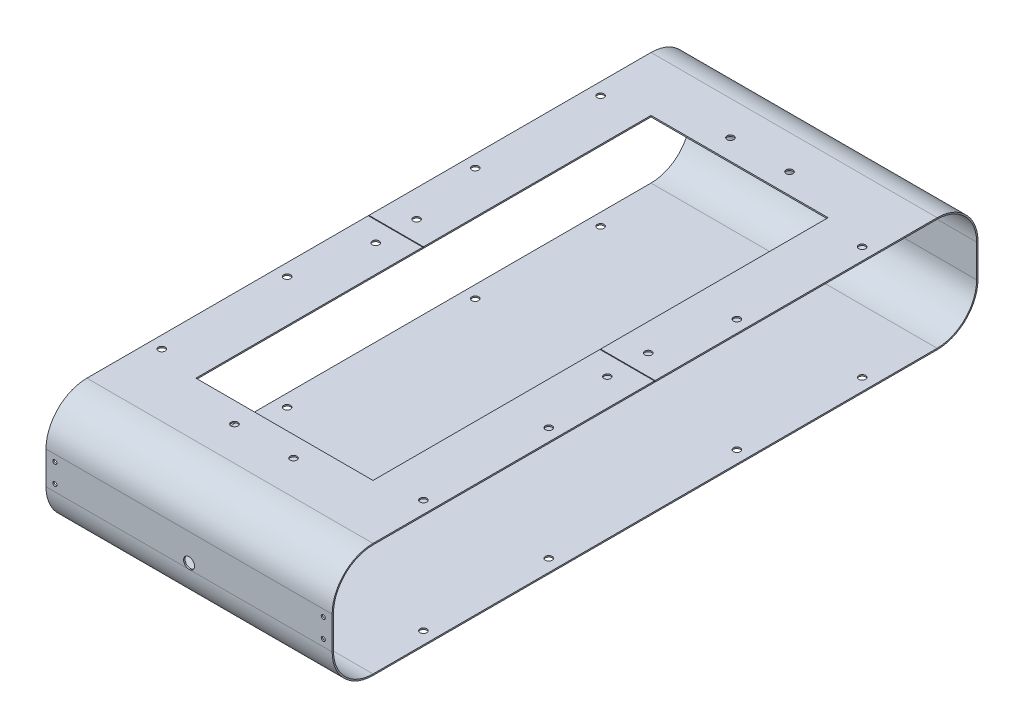
SolidWorks part; units mm, degrees
material "3.0205 (EN-AW 1200)"
ref_plane "Alzado" through (0, 0, 0) normal (0, 0, 1) x (1, 0, 0)
ref_plane "Planta" through (0, 0, 0) normal (0, 1, 0) x (1, 0, 0)
ref_plane "Vista lateral" through (0, 0, 0) normal (1, 0, 0) x (0, 0, -1)
sketch "Croquis1" plane through (0, 0, 0) normal (1, 0, 0) x (0, 0, -1)
  line L1 (207, -42) -> (-207, -42)
  line L2 (237, -12) -> (237, 12)
  line L3 (207, 42) -> (-207, 42)
  line L4 (-237, -12) -> (-237, 12)
  line L5 (237, -42) -> (-237, 42) construction
  line L6 (237, 42) -> (-237, -42) construction
  arc A4 (-237, 12) -> (-207, 42) centre (-207, 12) cw
  arc A5 (207, -42) -> (237, -12) centre (207, -12) ccw
  arc A6 (207, 42) -> (237, 12) centre (207, 12) cw
  arc A7 (-237, -12) -> (-207, -42) centre (-207, -12) ccw
  point P0 (0, 0)
  dimension "D4" = 30
  dimension "D5" = 30
  dimension "D1" = 474
  dimension "D2" = 84
extrude "Saliente-Extruir1" add sketch "Croquis1" along normal mid plane 220
shell "Vaciado2" thickness 1
sketch "Croquis2" plane through (110, 0, 0) normal (1, 0, 0) x (0, 0, -1)
  line L8 (237, -12) -> (237, 12)
  line L9 (207, 42) -> (-207, 42)
  line L10 (-237, 12) -> (-237, -12)
  line L11 (-207, -42) -> (207, -42)
  line L12 (237, -12) -> (237, 12)
  line L13 (207, 42) -> (-207, 42)
  line L14 (-237, 12) -> (-237, -12)
  line L15 (-207, -42) -> (207, -42)
  arc A8 (207, -42) -> (237, -12) centre (207, -12) ccw
  arc A9 (237, 12) -> (207, 42) centre (207, 12) ccw
  arc A10 (-207, 42) -> (-237, 12) centre (-207, 12) ccw
  arc A11 (-237, -12) -> (-207, -42) centre (-207, -12) ccw
  arc A12 (207, -42) -> (237, -12) centre (207, -12) ccw
  arc A13 (237, 12) -> (207, 42) centre (207, 12) ccw
  arc A14 (-207, 42) -> (-237, 12) centre (-207, 12) ccw
  arc A15 (-237, -12) -> (-207, -42) centre (-207, -12) ccw
  dimension "D1" = 0
sketch "Croquis5" plane through (0, 0, 0) normal (1, 0, 0) x (0, 0, -1)
  line L27 (-237, 12) -> (-237, -12)
  line L28 (-207, -42) -> (207, -42)
  line L29 (237, -12) -> (237, 12)
  line L30 (207, 42) -> (-207, 42)
  line L31 (-237, 12) -> (-237, -12)
  line L32 (-207, -42) -> (207, -42)
  line L33 (237, -12) -> (237, 12)
  line L34 (207, 42) -> (-207, 42)
  arc A31 (-237, -12) -> (-207, -42) centre (-207, -12) ccw
  arc A32 (207, -42) -> (237, -12) centre (207, -12) ccw
  arc A33 (237, 12) -> (207, 42) centre (207, 12) ccw
  arc A34 (-207, 42) -> (-237, 12) centre (-207, 12) ccw
  arc A35 (-237, -12) -> (-207, -42) centre (-207, -12) ccw
  arc A36 (207, -42) -> (237, -12) centre (207, -12) ccw
  arc A37 (237, 12) -> (207, 42) centre (207, 12) ccw
  arc A38 (-207, 42) -> (-237, 12) centre (-207, 12) ccw
  dimension "D1" = 0
sketch "Croquis6" plane through (-110, 0, 0) normal (-1, 0, 0) x (0, 0, 1)
  line L8 (207, 42) -> (-207, 42)
  line L9 (237, -12) -> (237, 12)
  line L10 (-207, -42) -> (207, -42)
  line L11 (-237, 12) -> (-237, -12)
  line L12 (207, 42) -> (-207, 42)
  line L13 (237, -12) -> (237, 12)
  line L14 (-207, -42) -> (207, -42)
  line L15 (-237, 12) -> (-237, -12)
  arc A8 (237, 12) -> (207, 42) centre (207, 12) ccw
  arc A9 (207, -42) -> (237, -12) centre (207, -12) ccw
  arc A10 (-237, -12) -> (-207, -42) centre (-207, -12) ccw
  arc A11 (-207, 42) -> (-237, 12) centre (-207, 12) ccw
  arc A12 (237, 12) -> (207, 42) centre (207, 12) ccw
  arc A13 (207, -42) -> (237, -12) centre (207, -12) ccw
  arc A14 (-237, -12) -> (-207, -42) centre (-207, -12) ccw
  arc A15 (-207, 42) -> (-237, 12) centre (-207, 12) ccw
  dimension "D1" = 0
extrude "Cortar-Extruir1" cut sketch "Croquis6" against normal blind 10
sketch "Croquis7" plane through (0, 0, 237) normal (0, 0, 1) x (1, 0, 0)
  line L0 (82.1341, 15) -> (-72.1341, 15)
  line L1 (-72.1341, -15) -> (82.1341, -15)
  line L2 (-72.1341, 15) -> (82.1341, -15) construction
  line L3 (82.1341, 15) -> (-72.1341, -15) construction
  line L4 (110, 12) -> (-100, -12) construction
  arc A0 (-74.8961, 14.1673) -> (-74.8961, -14.1673) centre (-65.5, 0) ccw
  arc A1 (84.8961, -14.1673) -> (84.8961, 14.1673) centre (75.5, 0) ccw
  spline S0 degree 2 poles (-72.1341, 15) (-72.8713, 15) (-73.5765, 14.7873) (-74.2822, 14.5745) (-74.8961, 14.1673) knots 0 0 0 0.5 0.5 1 1 1
  spline S1 degree 2 poles (-74.8961, -14.1673) (-74.2818, -14.5748) (-73.5765, -14.7873) (-72.8707, -15) (-72.1341, -15) knots 0 0 0 0.5 0.5 1 1 1
  spline S2 degree 2 poles (82.1341, -15) (82.8713, -15) (83.5765, -14.7873) (84.2822, -14.5745) (84.8961, -14.1673) knots 0 0 0 0.5 0.5 1 1 1
  spline S3 degree 2 poles (84.8961, 14.1673) (84.2818, 14.5748) (83.5765, 14.7873) (82.8707, 15) (82.1341, 15) knots 0 0 0 0.5 0.5 1 1 1
  point P16 (5, 0)
  point P17 (5, 0)
sketch "Croquis8" plane through (0, 0, 237) normal (0, 0, 1) x (1, 0, 0)
  line L0 (110, 12) -> (103.5, 12) construction
  line L1 (110, 12) -> (-100, 12) construction
  line L2 (103.5, 12) -> (103.5, 7) construction
  line L3 (110, -12) -> (103.5, -12) construction
  line L4 (110, -12) -> (-100, -12) construction
  line L5 (103.5, -12) -> (103.5, -7) construction
  line L6 (5, 0) -> (5, 71.8665) construction
  line L7 (-72.1341, 15) -> (82.1341, -15) construction
  circle A0 centre (103.5, 7) radius 1.5
  circle A1 centre (103.5, -7) radius 1.5
  circle A2 centre (-93.5, -7) radius 1.5
  circle A3 centre (-93.5, 7) radius 1.5
  dimension "D3" = 3
  dimension "D6" = 3
  dimension "D1" = 6.5
  dimension "D2" = 5
  dimension "D4" = 6.5
  dimension "D5" = 5
extrude "Cortar-Extruir4" cut sketch "Croquis8" against normal blind 5
sketch "Croquis9" plane through (0, 0, 237) normal (0, 0, 1) x (1, 0, 0)
  line L0 (5, -12) -> (5, -4) construction
  line L1 (110, -12) -> (-100, -12) construction
  circle A0 centre (5, -8) radius 4
  dimension "D1" = 8
extrude "Cortar-Extruir5" cut sketch "Croquis9" against normal blind 5
sketch "Croquis10" plane through (0, 42, 0) normal (0, 1, 0) x (1, 0, 0)
  line L0 (110, 207) -> (101, 207) construction
  line L1 (110, 207) -> (-100, 207) construction
  line L2 (101, 207) -> (101, 161.01) construction
  line L3 (101, 161.01) -> (101, 69.01) construction
  line L4 (5, 207) -> (5, -207) construction
  line L5 (110, -207) -> (-100, -207) construction
  line L6 (5, 0) -> (-100, 0) construction
  line L7 (-100, -207) -> (-100, 207) construction
  line L8 (-91, 161.01) -> (-91, 69.01) construction
  line L9 (-91, 207) -> (-91, 161.01) construction
  line L10 (101, -161.01) -> (101, -69.01) construction
  line L11 (101, -207) -> (101, -161.01) construction
  line L12 (-91, -161.01) -> (-91, -69.01) construction
  circle A0 centre (101, 161.01) radius 2.5
  circle A1 centre (101, 69.01) radius 2.5
  circle A2 centre (-91, 69.01) radius 2.5
  circle A3 centre (-91, 161.01) radius 2.5
  circle A4 centre (101, -69.01) radius 2.5
  circle A5 centre (101, -161.01) radius 2.5
  circle A6 centre (-91, -161.01) radius 2.5
  circle A7 centre (-91, -69.01) radius 2.5
  dimension "D3" = 5
  dimension "D5" = 5
  dimension "D1" = 9
  dimension "D2" = 45.99
  dimension "D4" = 92
extrude "Cortar-Extruir6" cut sketch "Croquis10" against normal through all
sketch "Croquis11" plane through (0, 42, 0) normal (0, 1, 0) x (1, 0, 0)
  line L8 (-60, 167) -> (-60, -167)
  line L9 (-60, -167) -> (70, -167)
  line L10 (70, -167) -> (70, 167)
  line L11 (70, 167) -> (-60, 167)
  line L12 (-60, 167) -> (-60, -167)
  line L13 (-60, -167) -> (70, -167)
  line L14 (70, -167) -> (70, 167)
  line L15 (70, 167) -> (-60, 167)
  dimension "D1" = 40
extrude "Cortar-Extruir7" cut sketch "Croquis11" against normal blind 8
sketch "Croquis12" plane through (0, 42, 0) normal (0, 1, 0) x (1, 0, 0)
  line L0 (70, 167) -> (-60, 167) construction
  line L1 (-60, 167) -> (-16.6667, 167) construction
  line L2 (-16.6667, 167) -> (26.6667, 167) construction
  line L3 (26.6667, 167) -> (70, 167) construction
  line L4 (-16.6667, 167) -> (-16.6667, 182) construction
  line L5 (26.6667, 167) -> (26.6667, 182) construction
  line L6 (0, 0) -> (160.0626, 0) construction
  circle A0 centre (-16.6667, 182) radius 2.5
  circle A1 centre (26.6667, 182) radius 2.5
  circle A2 centre (26.6667, -182) radius 2.5
  circle A3 centre (-16.6667, -182) radius 2.5
  point P15 (-16.6667, -182)
  point P16 (26.6667, -182)
  dimension "D5" = 5
  dimension "D6" = 5
  dimension "D1" = 43.3333
  dimension "D2" = 43.3333
  dimension "D3" = 15
  dimension "D4" = 15
extrude "Cortar-Extruir8" cut sketch "Croquis12" against normal blind 8
sketch "Croquis13" plane through (0, 42, 0) normal (0, 1, 0) x (1, 0, 0)
  line L0 (0, 0) -> (-100, 0) construction
  line L1 (-100, -207) -> (-100, 207) construction
  line L2 (-60, 167) -> (-60, -167) construction
  line L3 (-100, 0) -> (-60, 0)
  line L4 (-100, 0) -> (-100, -0.5)
  line L5 (-100, -0.5) -> (-60, -0.5)
  line L6 (-60, 0) -> (-60, -0.5)
  line L7 (0, 0) -> (0, 83.4895) construction
  line L8 (5, 167) -> (5, -79.8783) construction
  line L9 (70, 167) -> (-60, 167) construction
  line L10 (10, 0) -> (110, 0) construction
  line L11 (70, 0) -> (70, -0.5)
  line L12 (110, -0.5) -> (70, -0.5)
  line L13 (110, 0) -> (110, -0.5)
  line L14 (110, 0) -> (70, 0)
  dimension "D1" = 0.5
extrude "Cortar-Extruir9" cut sketch "Croquis13" against normal blind 1
sketch "Croquis14" plane through (0, 42, 0) normal (0, 1, 0) x (1, 0, 0)
  line L0 (90, 0) -> (90, 15) construction
  line L1 (110, 0) -> (70, 0) construction
  line L2 (90, 0) -> (90, -15) construction
  line L3 (5, 167) -> (5, -69.3269) construction
  line L4 (70, 167) -> (-60, 167) construction
  line L5 (-80, 0) -> (-80, -15) construction
  line L6 (-80, 0) -> (-80, 15) construction
  circle A0 centre (90, 15) radius 2.5
  circle A1 centre (90, -15) radius 2.5
  circle A2 centre (-80, -15) radius 2.5
  circle A3 centre (-80, 15) radius 2.5
  dimension "D3" = 5
  dimension "D4" = 5
  dimension "D1" = 15
  dimension "D2" = 15
extrude "Cortar-Extruir10" cut sketch "Croquis14" against normal blind 1
sketch "Croquis15" plane through (0, 42, 0) normal (0, 1, 0) x (1, 0, 0)
  line L0 (5, 167) -> (5, -167) construction
  line L1 (70, 167) -> (-60, 167) construction
  line L2 (-60, -167) -> (70, -167) construction
ref_plane "Plano1" through (5, 0, 0) normal (1, 0, 0) x (0, 0, -1)
